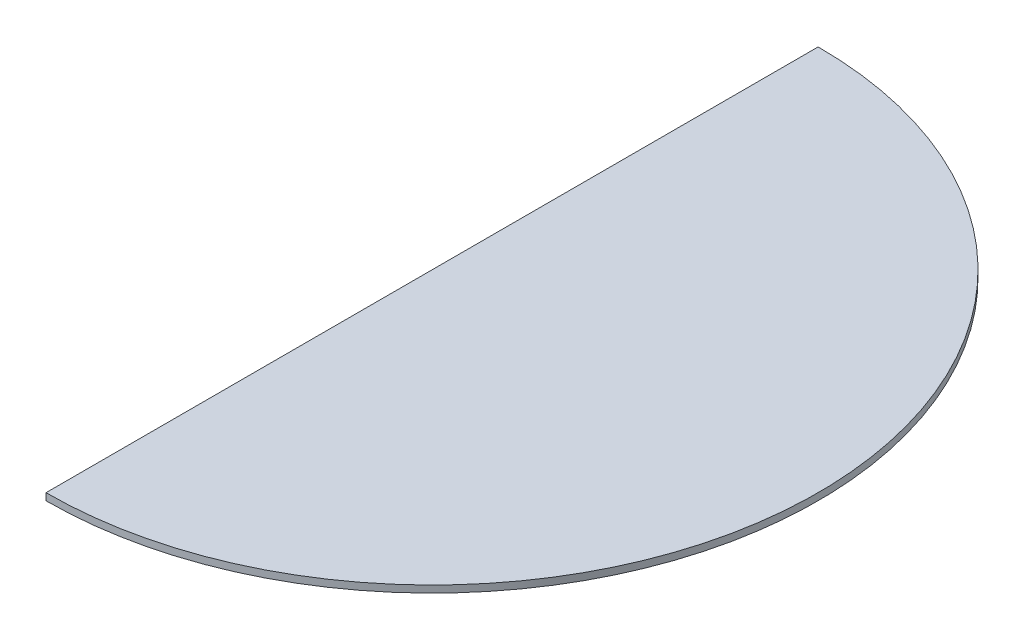
SolidWorks part; units mm, degrees
ref_plane "Plan de face" through (0, 0, 0) normal (0, 0, 1) x (1, 0, 0)
ref_plane "Plan de dessus" through (0, 0, 0) normal (0, 1, 0) x (1, 0, 0)
ref_plane "Plan de droite" through (0, 0, 0) normal (1, 0, 0) x (0, 0, -1)
sketch "Esquisse2" plane through (0, 0, 0) normal (0, 1, 0) x (1, 0, 0)
  line L0 (0, 1100) -> (0, 0)
  line L1 (0, 0) -> (0, -1100)
  arc A0 (0, 1100) -> (0, -1100) centre (0, 0) cw
  dimension "D1" = 1100
extrude "Boss.-Extru.1" add sketch "Esquisse2" along normal blind 20
